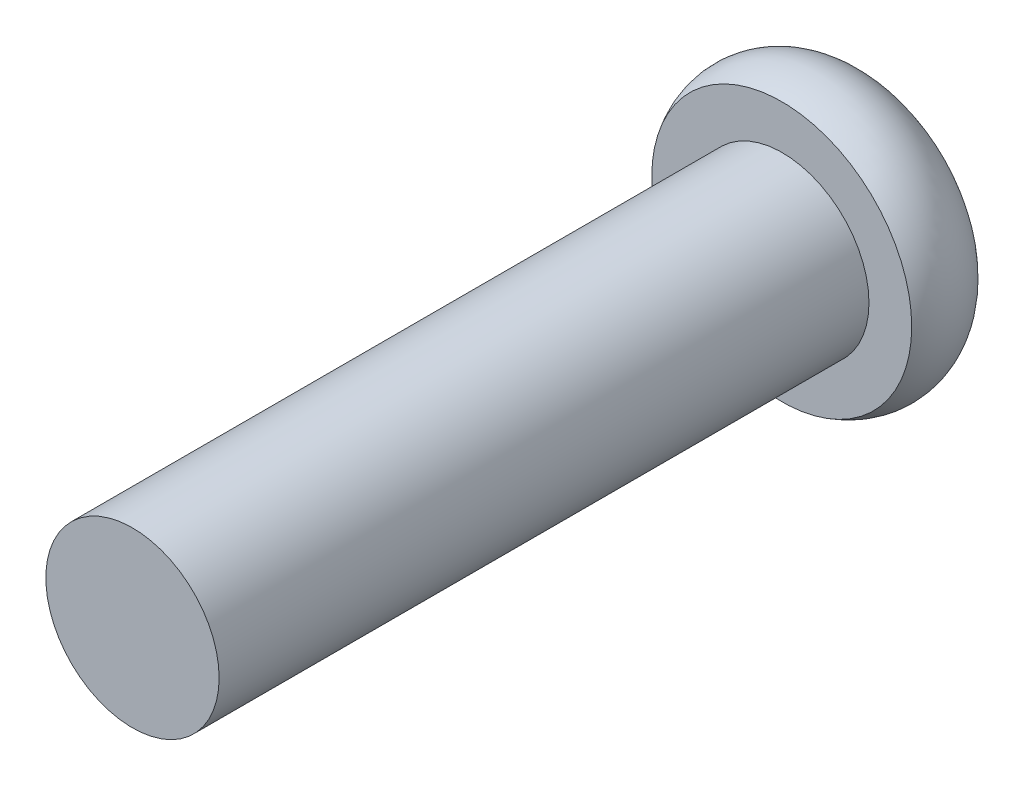
SolidWorks part; units mm, degrees
ref_plane "Front Plane" through (0, 0, 0) normal (0, 0, 1) x (1, 0, 0)
ref_plane "Top Plane" through (0, 0, 0) normal (0, 1, 0) x (1, 0, 0)
ref_plane "Right Plane" through (0, 0, 0) normal (1, 0, 0) x (0, 0, -1)
sketch "Sketch1" plane through (0, 0, 0) normal (0, 1, 0) x (1, 0, 0)
  line L0 (0, 0.6593) -> (0, 4.5218) construction
  line L3 (0, 0) -> (0, 2)
  line L4 (0, 0) -> (3, 0)
  line L5 (0, 2) -> (2.2983, 2)
  arc A0 (2.5735, 1.9174) -> (3, 0) centre (1.7961, 0.7384) cw
  arc A1 (2.5735, 1.9174) -> (2.2983, 2) centre (2.2983, 1.5) ccw
  dimension "D2" = 0.5
revolve "Revolve2" add sketch "Sketch1" angle 360 about L0
sketch "Sketch2" plane through (0, 0, -2) normal (0, 0, -1) x (-1, 0, 0)
  line L0 (0, 0) -> (2.5296, 0) construction
  line L1 (0, 0) -> (0, 1.7464) construction
  line L2 (0.5, -0.5) -> (2, -0.5)
  line L3 (-0.5, 2) -> (0.5, 2)
  line L4 (-0.5, 2) -> (-0.5, 0.5)
  line L5 (-0.5, -2) -> (0.5, -2)
  line L6 (0.5, 2) -> (0.5, 0.5)
  line L7 (0.5, 0.5) -> (2, 0.5)
  line L8 (0.5, -0.5) -> (0.5, -2)
  line L9 (-2, 0.5) -> (-0.5, 0.5)
  line L10 (-2, 0.5) -> (-2, -0.5)
  line L11 (-2, -0.5) -> (-0.5, -0.5)
  line L12 (2, 0.5) -> (2, -0.5)
  line L15 (-0.5, -0.5) -> (-0.5, -2)
  point P4 (0, 0)
  point P12 (0, 0)
  dimension "D1" = 0.5
  dimension "D2" = 2
  dimension "D3" = 2
  dimension "D4" = 2
  dimension "D5" = 0.5
  dimension "D6" = 0.5
  dimension "D7" = 0.5
  dimension "D8" = 0.5
extrude "Cut-Extrude1" cut sketch "Sketch2" against normal blind 2 draft 12
sketch "Sketch3" plane through (0, 0, 0) normal (0, 0, 1) x (1, 0, 0)
  circle A0 centre (0.0136, -0.0136) radius 2
extrude "Boss-Extrude1" add sketch "Sketch3" along normal blind 15
cosmetic thread "Cosmetic Thread2" parameters "D2"=2.439
